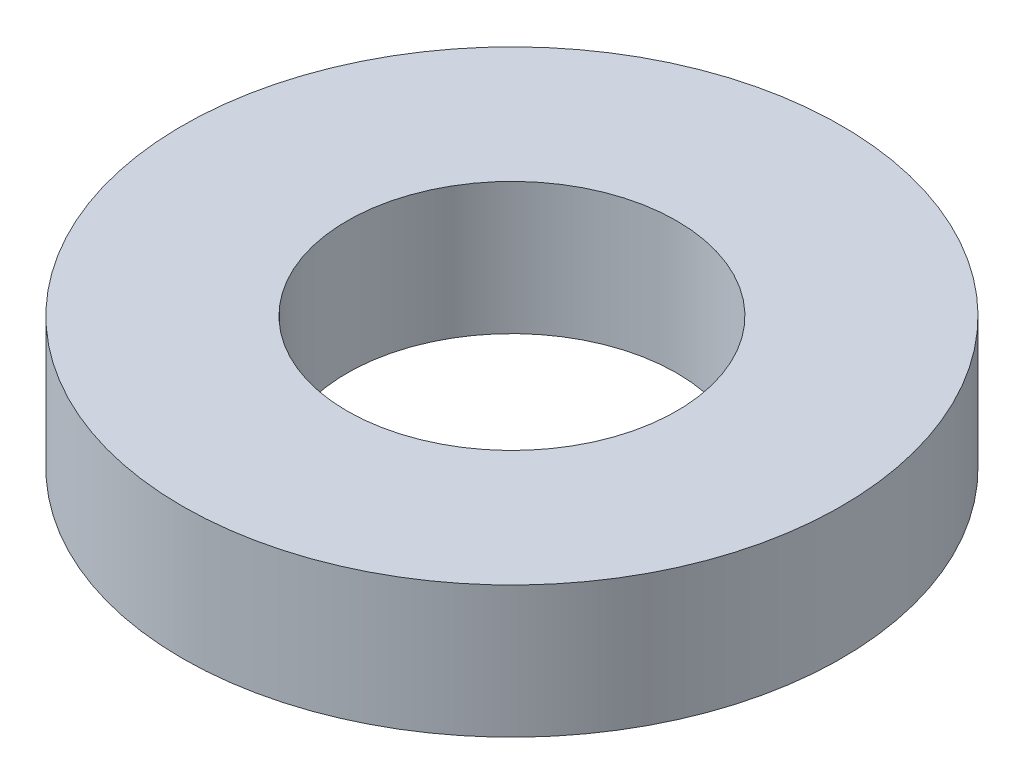
SolidWorks part; units mm, degrees
ref_plane "Front Plane" through (0, 0, 0) normal (0, 0, 1) x (1, 0, 0)
ref_plane "Top Plane" through (0, 0, 0) normal (0, 1, 0) x (1, 0, 0)
ref_plane "Right Plane" through (0, 0, 0) normal (1, 0, 0) x (0, 0, -1)
sketch "Sketch1" plane through (0, 0, 0) normal (0, 1, 0) x (1, 0, 0)
  circle A0 centre (0, 0) radius 10
  circle A1 centre (0, 0) radius 5
extrude "Boss-Extrude1" add sketch "Sketch1" along normal blind 4
